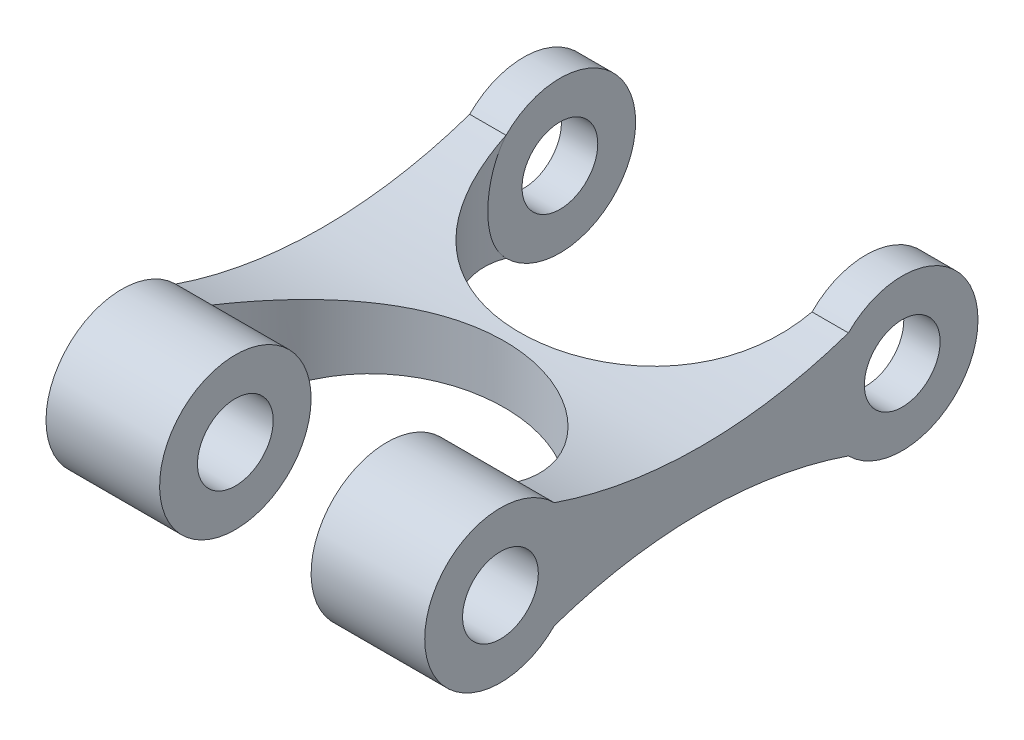
SolidWorks part; units mm, degrees
ref_plane "Front Plane" through (0, 0, 0) normal (0, 0, 1) x (1, 0, 0)
ref_plane "Top Plane" through (0, 0, 0) normal (0, 1, 0) x (1, 0, 0)
ref_plane "Right Plane" through (0, 0, 0) normal (1, 0, 0) x (0, 0, -1)
sketch "Sketch2" plane through (0, 0, 0) normal (1, 0, 0) x (0, 0, -1)
  line L0 (-6.6308, 0) -> (6.6308, 0)
  circle A0 centre (6.6308, 0) radius 2.5
  circle A1 centre (-6.6308, 0) radius 2.5
  circle A2 centre (-6.6308, 0) radius 1.25
  circle A3 centre (6.6308, 0) radius 1.25
  point P3 (0, 0)
  dimension "D2" = 5
  dimension "D3" = 2.5
  dimension "D1" = 13.2617
extrude "Boss-Extrude1" add sketch "Sketch2" along normal mid plane 12.5
sketch "Sketch3" plane through (0, 0, 0) normal (1, 0, 0) x (0, 0, -1)
  circle A0 centre (6.6308, 0) radius 2.5 construction
  circle A1 centre (6.6308, 0) radius 1.25 construction
  circle A2 centre (-6.6308, 0) radius 1.25 construction
  circle A3 centre (-6.6308, 0) radius 2.5 construction
  circle A4 centre (6.6308, 0) radius 2.5
  circle A5 centre (6.6308, 0) radius 1.25
  circle A6 centre (-6.6308, 0) radius 1.25
  circle A7 centre (-6.6308, 0) radius 2.5
extrude "Cut-Extrude1" cut sketch "Sketch3" against normal mid plane 10.1
sketch "Sketch4" plane through (0, 0, 0) normal (1, 0, 0) x (0, 0, -1)
  line L0 (-5.2366, 0) -> (4.1308, 0) construction
  circle A0 centre (6.6308, 0) radius 2.5 construction
  circle A1 centre (-6.6308, 0) radius 2.5 construction
  arc A2 (4.8537, 1.7583) -> (4.8537, -1.7583) centre (6.6308, 0) ccw
  arc A3 (-4.8537, -1.7583) -> (-4.8537, 1.7583) centre (-6.6308, 0) ccw
  arc A4 (-4.8537, 1.7583) -> (4.8537, 1.7583) centre (0, 15.8881) ccw
  arc A5 (-4.8537, -1.7583) -> (4.8537, -1.7583) centre (0, -15.8881) cw
extrude "Boss-Extrude2" add sketch "Sketch4" along normal mid plane 12.5
sketch "Sketch5" plane through (0, 0, 0) normal (0, 1, 0) x (1, 0, 0)
  line L0 (-5.05, 4.8537) -> (5.05, 4.8537)
  line L5 (5.05, -4.8537) -> (-5.05, -4.8537)
  arc A0 (-5.05, 4.8537) -> (5.05, 4.8537) centre (0, 5.3216) ccw
  arc A1 (-5.05, -4.8537) -> (5.05, -4.8537) centre (0, -5.3216) cw
  point P0 (0, 0)
extrude "Cut-Extrude2" cut sketch "Sketch5" against normal through all both and the other way through all contours L0 A0 | L5 A1
sketch "Sketch6" plane through (-5.05, 0, 0) normal (1, 0, 0) x (0, 0, -1)
  circle A0 centre (-6.6308, 0) radius 1.25 construction
  circle A1 centre (-6.6308, 0) radius 1.25
  arc A2 (-4.8537, 1.7583) -> (-4.8537, -1.7583) centre (-6.6308, 0) ccw
  arc A3 (-4.8537, -1.7583) -> (-4.8537, 1.7583) centre (-6.6308, 0) ccw
  arc A4 (-4.8537, 1.7583) -> (-4.8537, -1.7583) centre (-6.6308, 0) ccw
  arc A5 (-4.8537, -1.7583) -> (-4.8537, 1.7583) centre (-6.6308, 0) ccw
  dimension "D1" = 0
extrude "Boss-Extrude3" add sketch "Sketch6" along normal blind 11.001
sketch "Sketch7" plane through (0, 0, 0) normal (1, 0, 0) x (0, 0, -1)
  circle A2 centre (-6.6308, 0) radius 2.5
  circle A5 centre (-6.6308, 0) radius 1.25
extrude "Cut-Extrude3" cut sketch "Sketch7" against normal mid plane 5
scale "Scale1" scale about centroid uniform scaling yes scale factor 1.5
